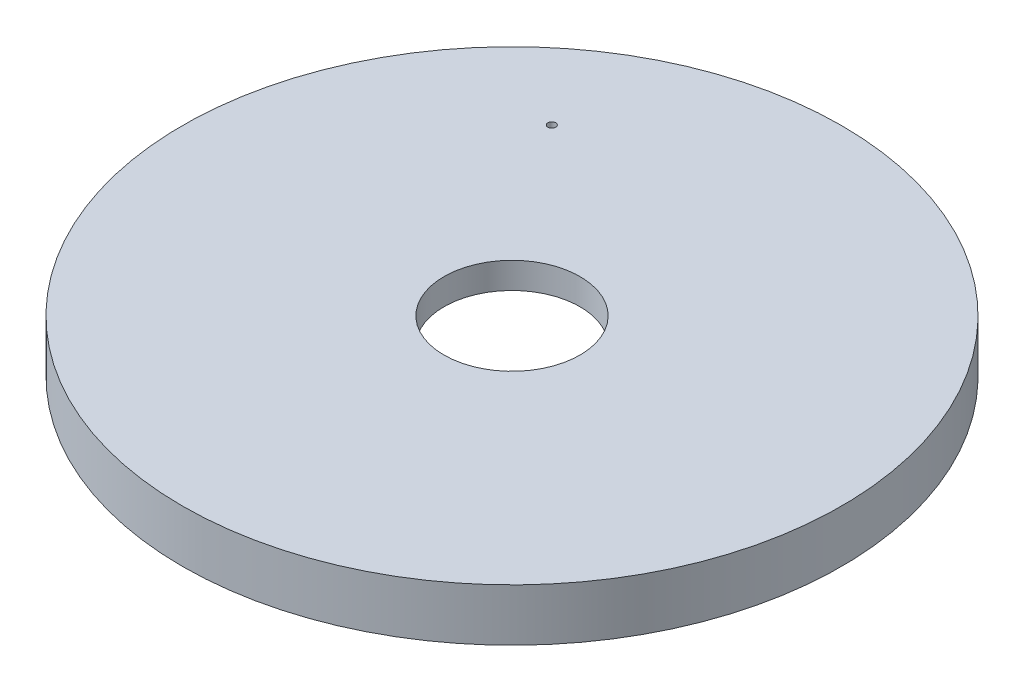
SolidWorks part; units mm, degrees
material "HYPALON"
ref_plane "Płaszczyzna przednia" through (0, 0, 0) normal (0, 0, 1) x (1, 0, 0)
ref_plane "Płaszczyzna górna" through (0, 0, 0) normal (0, 1, 0) x (1, 0, 0)
ref_plane "Płaszczyzna prawa" through (0, 0, 0) normal (1, 0, 0) x (0, 0, -1)
sketch "Szkic1" plane through (0, 0, 0) normal (0, 0, 1) x (1, 0, 0)
  line L0 (13, 2.5) -> (63, 2.5)
  line L1 (63, 2.5) -> (63, -7.5)
  line L2 (63, -7.5) -> (31.6603, -7.5)
  line L3 (31.6603, -7.5) -> (13, -2.5)
  line L4 (13, -2.5) -> (13, 2.5)
  line L5 (0, 24.6083) -> (0, -34.5814) construction
  point P8 (13, 0)
  dimension "D1" = 13
  dimension "D2" = 63
  dimension "D3" = 165
  dimension "D4" = 5
  dimension "D5" = 10
revolve "Obrót1" add sketch "Szkic1" angle 360 about L5
sketch "Szkic2" plane through (0, 0, 0) normal (0, 1, 0) x (1, 0, 0)
  line L0 (-27.786, 35.3969) -> (0, 0) construction
  line L1 (0, 0) -> (33.1748, -42.2618) construction
  circle A0 centre (-27.786, 35.3969) radius 0.75
  dimension "D1" = 45
  dimension "D2" = 1.5
extrude "Wytnij-wyciągnięcie2" cut sketch "Szkic2" against normal mid plane 30
